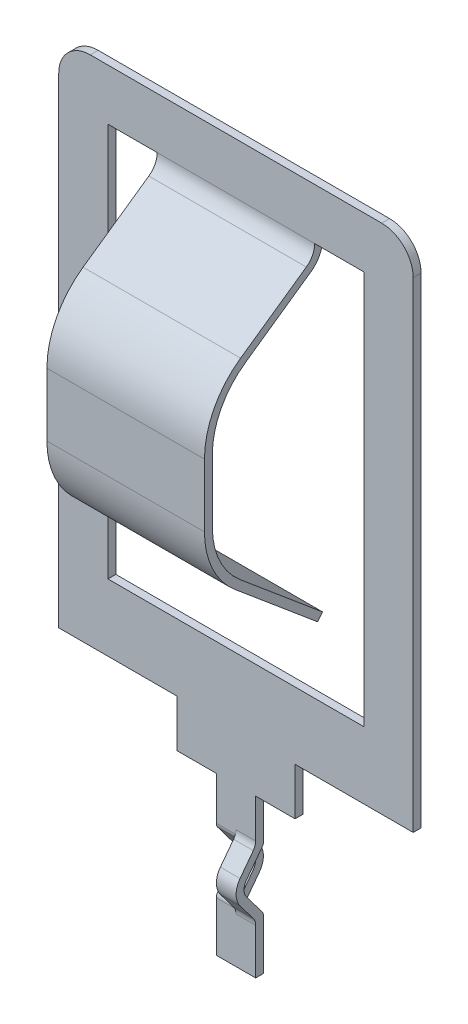
SolidWorks part; units mm, degrees
ref_plane "Спереди" through (0, 0, 0) normal (0, 0, 1) x (1, 0, 0)
ref_plane "Сверху" through (0, 0, 0) normal (0, 1, 0) x (1, 0, 0)
ref_plane "Справа" through (0, 0, 0) normal (1, 0, 0) x (0, 0, -1)
sketch "Sketch1" plane through (0, 0, 0) normal (0, 0, 1) x (1, 0, 0)
  line L0 (-4.5, 0) -> (4.5, 0)
  line L1 (4.5, 0) -> (4.5, -13)
  line L2 (-4.5, 0) -> (-4.5, -13)
  line L3 (4.5, -13) -> (1.5, -13)
  line L4 (-4.5, -13) -> (-1.5, -13)
  line L5 (-1.5, -13) -> (-1.5, -14.2)
  line L6 (1.5, -13) -> (1.5, -14.2)
  line L7 (-1.5, -14.2) -> (1.5, -14.2)
  line L8 (-3.25, -1.3) -> (-4.5, -1.3) construction
  line L9 (-3.25, -1.3) -> (3.25, -1.3)
  line L10 (-3.25, -1.3) -> (-3.25, -11.3)
  line L11 (-3.25, -11.3) -> (3.25, -11.3)
  line L12 (3.25, -1.3) -> (3.25, -11.3)
  line L13 (3.25, -1.3) -> (4.5, -1.3) construction
  dimension "D1" = 9
  dimension "D2" = 13
  dimension "D3" = 3
  dimension "D4" = 1.2
  dimension "D5" = 1.3
  dimension "D6" = 6.5
  dimension "D7" = 10
extrude "Boss-Extrude1" add sketch "Sketch1" along normal blind 0.2
ref_plane "Plane1" through (0, 0, 0) normal (-1, 0, 0) x (0, 0, 1)
sketch "Sketch2" plane through (0, 0, 0) normal (-1, 0, 0) x (0, 0, 1)
  line L0 (2.8, -4.6407) -> (2.8, -6.2407)
  line L1 (0.2, -1.3914) -> (0.2, 0.004) construction
  line L2 (0.2, -13) -> (0.2, 0) construction
  line L3 (0, -1.3) -> (0, 0.1764) construction
  line L5 (0.2, 0) -> (0, 0) construction
  line L6 (0.1286, -9.6532) -> (0, -9.5)
  line L7 (0.2985, -1.8734) -> (1.968, -3.0424)
  line L8 (2.103, -7.7354) -> (0, -9.5)
  line L9 (0.2, -1.3) -> (0, -1.3)
  line L11 (0.4132, -1.7096) -> (2.0827, -2.8786)
  line L12 (3, -4.6407) -> (3, -6.2407)
  line L13 (2.2316, -7.8886) -> (0.1286, -9.6532)
  arc A0 (0, -1.3) -> (0.2985, -1.8734) centre (0.7, -1.3) ccw
  arc A1 (1.968, -3.0424) -> (2.8, -4.6407) centre (0.8488, -4.6407) cw
  arc A2 (2.8, -6.2407) -> (2.103, -7.7354) centre (0.8488, -6.2407) cw
  arc A3 (0.2, -1.3) -> (0.4132, -1.7096) centre (0.7, -1.3) ccw
  arc A4 (2.0827, -2.8786) -> (3, -4.6407) centre (0.8488, -4.6407) cw
  arc A5 (3, -6.2407) -> (2.2316, -7.8886) centre (0.8488, -6.2407) cw
  dimension "D2" = 0.2
  dimension "D3" = 0.2
  dimension "D5" = 2.8
  dimension "D6" = 1.6
  dimension "D7" = 0.5
  dimension "D8" = 125
  dimension "D9" = 130
  dimension "D4" = 0.2
  dimension "D1" = 9.5
extrude "Boss-Extrude2" add sketch "Sketch2" along normal mid plane 4
sketch "Sketch4" plane through (0, 0, 0) normal (-1, 0, 0) x (0, 0, 1)
  line L0 (0.2, -14.2139) -> (0.2, -16.479) construction
  line L1 (0, -14.2524) -> (0, -14.885) construction
  line L2 (0.2, -14.2) -> (0, -14.2)
  line L3 (0, -14.2) -> (0, -15.2958)
  line L4 (0.4362, -15.9345) -> (0.0353, -15.4014)
  line L5 (0.4362, -16.2951) -> (0.0353, -16.8282)
  line L6 (0, -16.9338) -> (0, -18.2)
  line L7 (0.2, -17.0422) -> (0.2, -18.2)
  line L8 (0.2, -14.2) -> (0.2, -15.1874)
  line L9 (0.5961, -15.8142) -> (0.2602, -15.3678)
  line L10 (0.5961, -16.4153) -> (0.2602, -16.8618)
  line L11 (0.2, -18.2) -> (0, -18.2)
  arc A0 (0, -15.2958) -> (0.0353, -15.4014) centre (0.1757, -15.2958) ccw
  arc A1 (0.4362, -15.9345) -> (0.4362, -16.2951) centre (0.1965, -16.1148) cw
  arc A2 (0.0353, -16.8282) -> (0, -16.9338) centre (0.1757, -16.9338) ccw
  arc A3 (0.2602, -16.8618) -> (0.2, -17.0422) centre (0.5, -17.0422) ccw
  arc A4 (0.5961, -15.8142) -> (0.5961, -16.4153) centre (0.1965, -16.1148) cw
  arc A5 (0.2, -15.1874) -> (0.2602, -15.3678) centre (0.5, -15.1874) ccw
  dimension "D1" = 4
  dimension "D2" = 0.5
  dimension "D5" = 0.3
  dimension "D6" = 0.393
  dimension "D3" = 0.2
  dimension "D4" = 0.2
extrude "Boss-Extrude3" add sketch "Sketch4" against normal blind 0.5
ref_plane "Plane2" through (0, 0, 0.1) normal (0, 0, -1) x (-1, 0, 0)
fillet "Fillet1" radius 0.8 2 edges at (4.5, 0, 0.1) (-4.5, 0, 0.1)
sketch "Sketch7" plane through (0, 0, 0) normal (-1, 0, 0) x (0, 0, 1)
  line L0 (0.0353, -15.4014) -> (0.4362, -15.9345) construction
  line L2 (0.4362, -16.2951) -> (0.0353, -16.8282) construction
  line L3 (0.2602, -16.8618) -> (0.5961, -16.4153) construction
  line L4 (0.5961, -15.8142) -> (0.2602, -15.3678) construction
  line L5 (0, -14.2) -> (0, -15.2958) construction
  line L6 (0, -16.9338) -> (0, -18.2) construction
  line L13 (0.1, -14.2) -> (0.1, -18.2) construction
  line L14 (0, -14.2) -> (0.2, -14.2)
  line L15 (0.2, -18.2) -> (0, -18.2)
  line L16 (0, -18.2) -> (0, -17.0422)
  line L17 (-0.0602, -16.8618) -> (-0.3961, -16.4153)
  line L18 (-0.3961, -15.8142) -> (-0.0602, -15.3678)
  line L19 (0, -15.1874) -> (0, -14.2)
  line L20 (0.2, -14.2) -> (0.2, -15.2958)
  line L21 (0.2, -16.9338) -> (0.2, -18.2)
  line L22 (-0.2362, -16.2951) -> (0.1647, -16.8282)
  line L23 (0.1647, -15.4014) -> (-0.2362, -15.9345)
  arc A0 (0.4362, -16.2951) -> (0.4362, -15.9345) centre (0.1965, -16.1148) ccw construction
  arc A1 (0.5961, -16.4153) -> (0.5961, -15.8142) centre (0.1965, -16.1148) ccw construction
  arc A2 (0.2, -15.1874) -> (0.2602, -15.3678) centre (0.5, -15.1874) ccw construction
  arc A3 (0, -15.2958) -> (0.0353, -15.4014) centre (0.1757, -15.2958) ccw construction
  arc A4 (0.2602, -16.8618) -> (0.2, -17.0422) centre (0.5, -17.0422) ccw construction
  arc A5 (0.0353, -16.8282) -> (0, -16.9338) centre (0.1757, -16.9338) ccw construction
  arc A6 (0, -17.0422) -> (-0.0602, -16.8618) centre (-0.3, -17.0422) ccw
  arc A7 (-0.3961, -16.4153) -> (-0.3961, -15.8142) centre (0.0035, -16.1148) cw
  arc A8 (-0.0602, -15.3678) -> (0, -15.1874) centre (-0.3, -15.1874) ccw
  arc A9 (0.2, -15.2958) -> (0.1647, -15.4014) centre (0.0243, -15.2958) cw
  arc A10 (0.1647, -16.8282) -> (0.2, -16.9338) centre (0.0243, -16.9338) cw
  arc A11 (-0.2362, -15.9345) -> (-0.2362, -16.2951) centre (0.0035, -16.1148) ccw
extrude "Boss-Extrude7" add sketch "Sketch7" along normal blind 0.5
